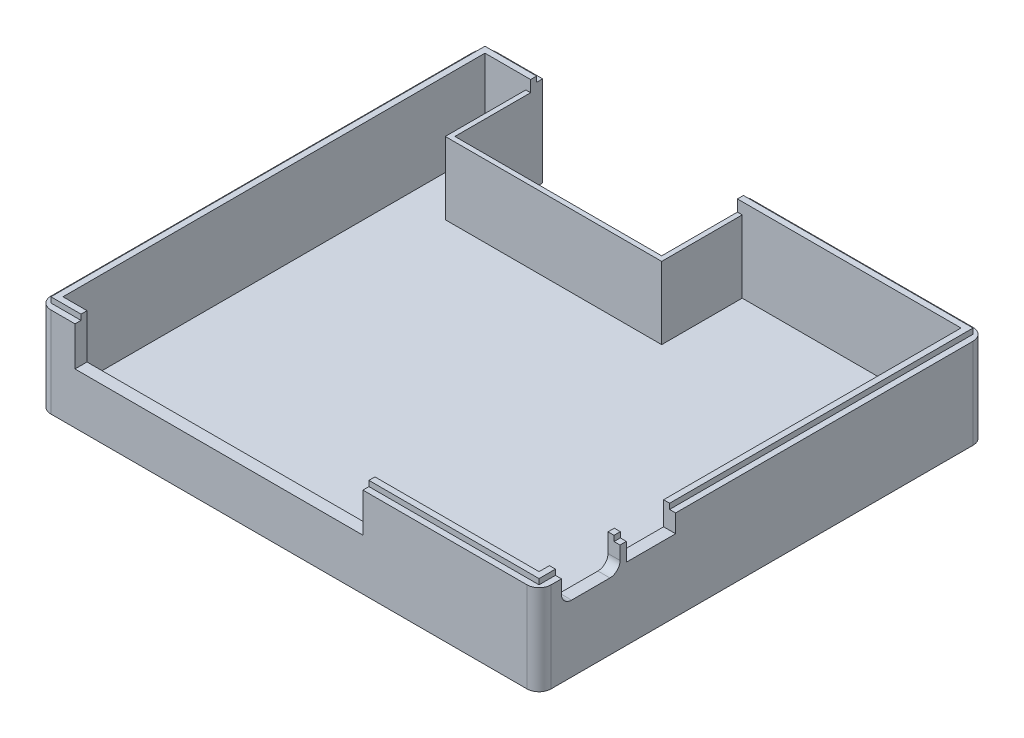
SolidWorks part; units mm, degrees
ref_plane "Front Plane" through (0, 0, 0) normal (0, 0, 1) x (1, 0, 0)
ref_plane "Top Plane" through (0, 0, 0) normal (0, 1, 0) x (1, 0, 0)
ref_plane "Right Plane" through (0, 0, 0) normal (1, 0, 0) x (0, 0, -1)
sketch "Sketch1" plane through (0, 0, 0) normal (0, 1, 0) x (1, 0, 0)
  line L1 (0, 0) -> (83.2, 0)
  line L2 (0, 0) -> (0, 74.2)
  line L3 (0, 74.2) -> (83.2, 74.2)
  line L4 (83.2, 0) -> (83.2, 74.2)
  dimension "D1" = 74.2
  dimension "D2" = 83.2
extrude "Boss-Extrude1" add sketch "Sketch1" along normal blind 15
shell "Shell1" thickness 2
sketch "Sketch2" plane through (0, 0, -2) normal (0, 0, -1) x (-1, 0, 0)
  line L0 (-2, 15) -> (-2, 2) construction
  line L1 (-6, 8.5) -> (-53.9, 8.5)
  line L2 (-6, 8.5) -> (-6, 15)
  line L3 (-6, 15) -> (-53.9, 15)
  line L4 (-53.9, 8.5) -> (-53.9, 15)
  line L6 (-2, 15) -> (-81.2, 15) construction
  dimension "D1" = 4
  dimension "D2" = 47.9
  dimension "D3" = 6.5
extrude "Cut-Extrude1" cut sketch "Sketch2" against normal through all
sketch "Sketch3" plane through (81.2, 0, 0) normal (-1, 0, 0) x (0, 0, 1)
  line L0 (-13.07, 12.775) -> (-13.07, 13.375) construction
  line L1 (-13.07, 12.775) -> (-13.07, 13.375) construction
  line L2 (-5.41, 11.495) -> (-11.79, 11.495) construction
  line L3 (-5.41, 11.495) -> (-11.79, 11.495) construction
  line L12 (-4.13, 13.375) -> (-4.13, 12.775) construction
  line L13 (-4.13, 13.375) -> (-4.13, 12.775) construction
  line L14 (-5.41, 14.655) -> (-11.79, 14.655) construction
  line L15 (-13.47, 12.775) -> (-13.47, 13.375)
  line L17 (-3.73, 13.375) -> (-3.73, 12.775)
  line L18 (-5.41, 11.095) -> (-11.79, 11.095)
  line L19 (-13.47, 13.375) -> (-13.47, 15)
  line L20 (-2, 15) -> (-72.2, 15) construction
  line L21 (-13.47, 15) -> (-3.73, 15)
  line L22 (-3.73, 15) -> (-3.73, 13.375)
  line L24 (-5.41, 15.055) -> (-11.79, 15.055) construction
  arc A0 (-13.07, 12.775) -> (-11.79, 11.495) centre (-11.79, 12.775) ccw construction
  arc A1 (-11.79, 14.655) -> (-13.07, 13.375) centre (-11.79, 13.375) ccw construction
  arc A2 (-13.07, 12.775) -> (-11.79, 11.495) centre (-11.79, 12.775) ccw construction
  arc A3 (-11.79, 14.655) -> (-13.07, 13.375) centre (-11.79, 13.375) ccw construction
  arc A4 (-5.41, 11.495) -> (-4.13, 12.775) centre (-5.41, 12.775) ccw construction
  arc A5 (-5.41, 11.495) -> (-4.13, 12.775) centre (-5.41, 12.775) ccw construction
  arc A6 (-4.13, 13.375) -> (-5.41, 14.655) centre (-5.41, 13.375) ccw construction
  arc A7 (-4.13, 13.375) -> (-5.41, 14.655) centre (-5.41, 13.375) ccw construction
  arc A10 (-5.41, 11.095) -> (-3.73, 12.775) centre (-5.41, 12.775) ccw
  arc A11 (-13.47, 12.775) -> (-11.79, 11.095) centre (-11.79, 12.775) ccw
  arc A12 (-11.79, 15.055) -> (-13.47, 13.375) centre (-11.79, 13.375) ccw construction
  arc A13 (-3.73, 13.375) -> (-5.41, 15.055) centre (-5.41, 13.375) ccw construction
  dimension "D1" = 0.4
extrude "Cut-Extrude3" cut sketch "Sketch3" against normal through all contours L15 L19 L21 L22 L17 A10 L18 A11
sketch "Sketch4" plane through (81.2, 0, 0) normal (-1, 0, 0) x (0, 0, 1)
  line L0 (-13.47, 15) -> (-72.2, 15) construction
  line L1 (-14.52, 15) -> (-22.72, 15)
  line L2 (-14.52, 15) -> (-14.52, 12)
  line L3 (-14.52, 12) -> (-22.72, 12)
  line L4 (-22.72, 15) -> (-22.72, 12)
  line L5 (-13.47, 12.775) -> (-13.47, 15) construction
  dimension "D1" = 8.2
  dimension "D2" = 3
  dimension "D3" = 1.05
extrude "Cut-Extrude4" cut sketch "Sketch4" against normal through all
sketch "Sketch5" plane through (0, 2, 0) normal (0, 1, 0) x (1, 0, 0)
  line L0 (2, 2) -> (81.2, 2) construction
  line L1 (81.2, 2) -> (81.2, 72.2) construction
  circle A0 centre (77.9, 27) radius 1.5
  dimension "D1" = 25
  dimension "D2" = 3.3
  dimension "D3" = 3
extrude "Cut-Extrude5" cut sketch "Sketch5" against normal through all
sketch "Sketch6" plane through (0, 0, 0) normal (0, -1, 0) x (1, 0, 0)
  line L0 (83.2, -74.2) -> (0, -74.2) construction
  line L1 (9.6, -74.2) -> (44, -74.2)
  line L2 (9.6, -74.2) -> (9.6, -59.6)
  line L3 (9.6, -59.6) -> (44, -59.6)
  line L4 (44, -74.2) -> (44, -59.6)
  line L5 (0, -74.2) -> (0, 0) construction
  dimension "D1" = 9.6
  dimension "D2" = 44
  dimension "D3" = 14.6
extrude "Cut-Extrude6" cut sketch "Sketch6" against normal through all
sketch "Sketch7" plane through (0, 2, 0) normal (0, 1, 0) x (1, 0, 0)
  line L0 (44, 72.2) -> (44, 59.6) construction
  line L1 (44, 59.6) -> (9.6, 59.6) construction
  line L2 (9.6, 59.6) -> (9.6, 72.2) construction
  line L3 (44, 72.2) -> (44, 59.6)
  line L4 (44, 59.6) -> (9.6, 59.6)
  line L5 (9.6, 59.6) -> (9.6, 72.2)
  line L6 (44.8, 72.2) -> (44.8, 58.8)
  line L7 (44.8, 58.8) -> (8.8, 58.8)
  line L8 (8.8, 58.8) -> (8.8, 72.2)
  line L9 (8.8, 72.2) -> (9.6, 72.2)
  line L10 (44, 72.2) -> (44.8, 72.2)
  dimension "D1" = 0.8
extrude "Boss-Extrude2" add sketch "Sketch7" along normal blind 12
sketch "Sketch9" plane through (0, 15, 0) normal (0, 1, 0) x (1, 0, 0)
  line L0 (9.6, 72.2) -> (2, 72.2) construction
  line L1 (2, 2) -> (6, 2) construction
  line L2 (2, 72.2) -> (2, 2) construction
  line L3 (9.6, 72.2) -> (2, 72.2)
  line L4 (2, 2) -> (6, 2)
  line L5 (2, 72.2) -> (2, 2)
  line L6 (53.9, 2) -> (81.2, 2) construction
  line L7 (81.2, 2) -> (81.2, 3.73) construction
  line L8 (81.2, 13.47) -> (81.2, 14.52) construction
  line L9 (81.2, 22.72) -> (81.2, 72.2) construction
  line L10 (81.2, 72.2) -> (44, 72.2) construction
  line L11 (53.9, 2) -> (81.2, 2)
  line L12 (81.2, 2) -> (81.2, 3.73)
  line L13 (81.2, 13.47) -> (81.2, 14.52)
  line L14 (81.2, 22.72) -> (81.2, 72.2)
  line L15 (81.2, 72.2) -> (44, 72.2)
extrude "Extrude-Thin1" add sketch "Sketch9" along normal blind 0.9 thin
fillet "Fillet1" radius 2 4 edges at (0, 7.5, 0) (83.2, 7.5, 0) (83.2, 7.5, -74.2) (0, 7.5, -74.2)
